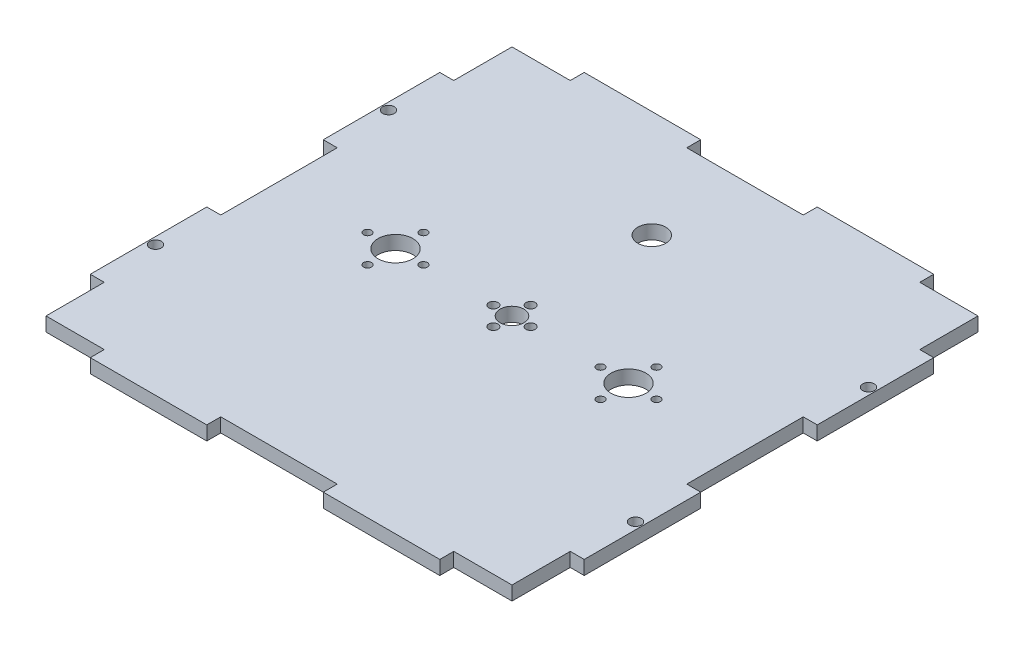
SolidWorks part; units mm, degrees
ref_plane "前视基准面" through (0, 0, 0) normal (0, 0, 1) x (1, 0, 0)
ref_plane "上视基准面" through (0, 0, 0) normal (0, 1, 0) x (1, 0, 0)
ref_plane "右视基准面" through (0, 0, 0) normal (1, 0, 0) x (0, 0, -1)
sketch "草图1" plane through (0, 0, 0) normal (0, 1, 0) x (1, 0, 0)
  line L0 (0, 200) -> (25, 200)
  line L1 (0, 0) -> (25, 0)
  line L2 (0, 0) -> (0, 25)
  line L3 (75, 200) -> (125, 200)
  line L4 (200, 0) -> (200, 25)
  line L5 (175, 200) -> (200, 200)
  line L6 (175, 200) -> (175, 206)
  line L7 (175, 206) -> (125, 206)
  line L8 (125, 206) -> (125, 200)
  line L9 (0, 175) -> (0, 200)
  line L10 (0, 75) -> (0, 125)
  line L11 (25, 200) -> (25, 206)
  line L12 (25, 206) -> (75, 206)
  line L13 (75, 206) -> (75, 200)
  line L14 (75, 0) -> (125, 0)
  line L15 (100, 100) -> (100, 160)
  line L16 (200, 25) -> (206, 25)
  line L17 (206, 25) -> (206, 75)
  line L18 (206, 75) -> (200, 75)
  line L19 (200, 100) -> (200, 125)
  line L20 (200, 75) -> (200, 125)
  line L21 (200, 175) -> (206, 175)
  line L22 (206, 175) -> (206, 125)
  line L23 (206, 125) -> (200, 125)
  line L24 (175, 0) -> (200, 0)
  line L25 (25, 0) -> (25, -6)
  line L26 (25, -6) -> (75, -6)
  line L27 (75, -6) -> (75, 0)
  line L28 (100, 0) -> (125, 0)
  line L29 (200, 175) -> (200, 200)
  line L30 (175, 0) -> (175, -6)
  line L31 (175, -6) -> (125, -6)
  line L32 (125, -6) -> (125, 0)
  line L33 (100, 100) -> (150, 100)
  line L34 (0, 175) -> (-6, 175)
  line L35 (-6, 175) -> (-6, 125)
  line L36 (-6, 125) -> (0, 125)
  line L37 (0, 100) -> (0, 75)
  line L39 (0, 25) -> (-6, 25)
  line L40 (-6, 25) -> (-6, 75)
  line L41 (-6, 75) -> (0, 75)
  circle A0 centre (100, 100) radius 5.1
  circle A1 centre (150, 112) radius 1.7
  circle A2 centre (100, 108) radius 2
  circle A3 centre (108, 100) radius 2
  circle A4 centre (100, 92) radius 2
  circle A5 centre (92, 100) radius 2
  circle A6 centre (50, 100) radius 7.5
  circle A7 centre (50, 112) radius 1.7
  circle A8 centre (62, 100) radius 1.7
  circle A9 centre (50, 88) radius 1.7
  circle A10 centre (38, 100) radius 1.7
  circle A11 centre (162, 100) radius 1.7
  circle A12 centre (138, 100) radius 1.7
  circle A13 centre (150, 88) radius 1.7
  circle A14 centre (150, 100) radius 7.5
  circle A15 centre (100, 160) radius 6
  circle A16 centre (-3, 150) radius 2.5
  circle A17 centre (203, 150) radius 2.5
  circle A18 centre (203, 50) radius 2.5
  circle A19 centre (-3, 50) radius 2.5
  point P46 (100, 100)
  point P66 (50, 100)
  point P74 (150, 100)
  dimension "D2" = 12
  dimension "D3" = 50
  dimension "D4" = 12
  dimension "D1" = 4
  dimension "D5" = 4
  dimension "D6" = 4
extrude "凸台-拉伸1" add sketch "草图1" along normal blind 6 contours L41 L40 L39 L2 L1 L25 L26 L27 L14 L32 L31 L30 L24 L4 L16 L17 L18 L20 L19 L23 L22 L21 L29 L5 L6 L7 L8 L3 L13 L12 L11 L0 L9 L34 L35 L36 L10
